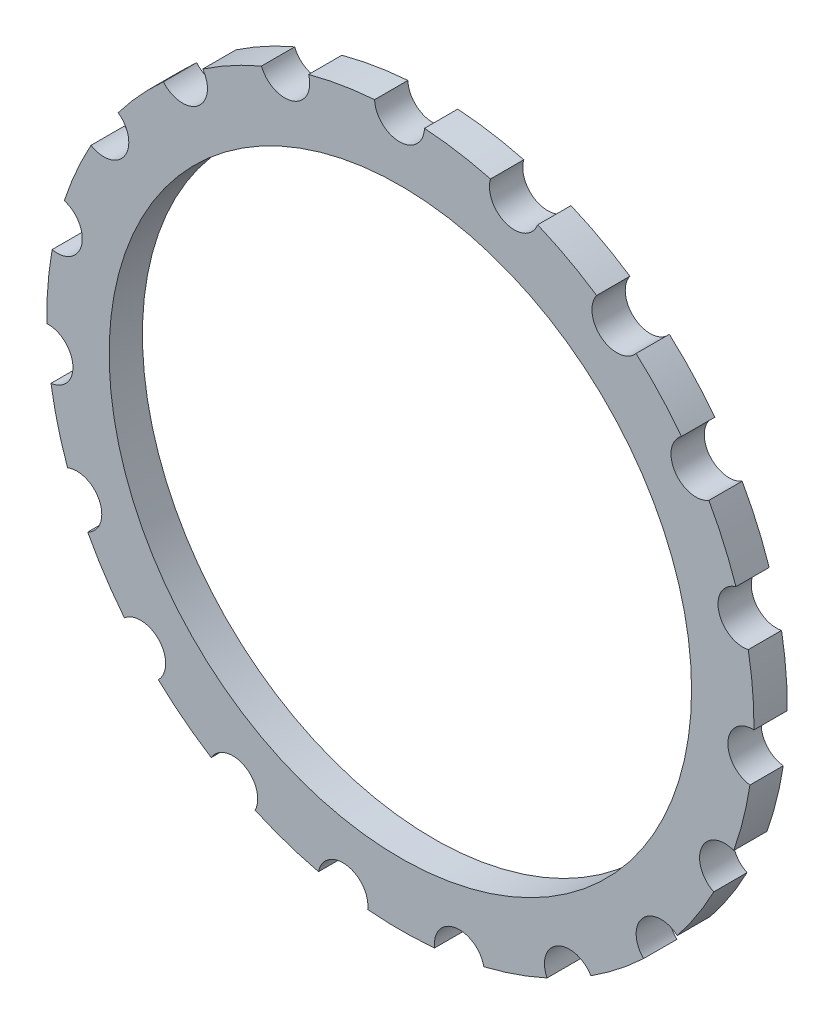
SolidWorks part; units mm, degrees
ref_plane "Front Plane" through (0, 0, 0) normal (0, 0, 1) x (1, 0, 0)
ref_plane "Top Plane" through (0, 0, 0) normal (0, 1, 0) x (1, 0, 0)
ref_plane "Right Plane" through (0, 0, 0) normal (1, 0, 0) x (0, 0, -1)
sketch "Sketch2" plane through (0, 0, 0) normal (0, 0, 1) x (1, 0, 0)
  circle A0 centre (0, 0) radius 7
  circle A1 centre (0, 0) radius 8.5
  dimension "D1" = 14
  dimension "D2" = 17
extrude "Boss-Extrude1" add sketch "Sketch2" along normal blind 0.8
sketch "Sketch3" plane through (0, 0, 0) normal (0, 0, 1) x (1, 0, 0)
  arc A0 (3.3018, 7.8325) -> (2.167, 8.2191) centre (2.7412, 8.0459) cw
  circle A1 centre (0, 0) radius 8.5 construction
extrude "Cut-Extrude1" cut sketch "Sketch3" against normal through all and the other way through all flip side to cut
pattern_circular "CirPattern2" count 19 over 360 about axis through (0, 0, 0) along (0, 0, 1) of "Cut-Extrude1"
